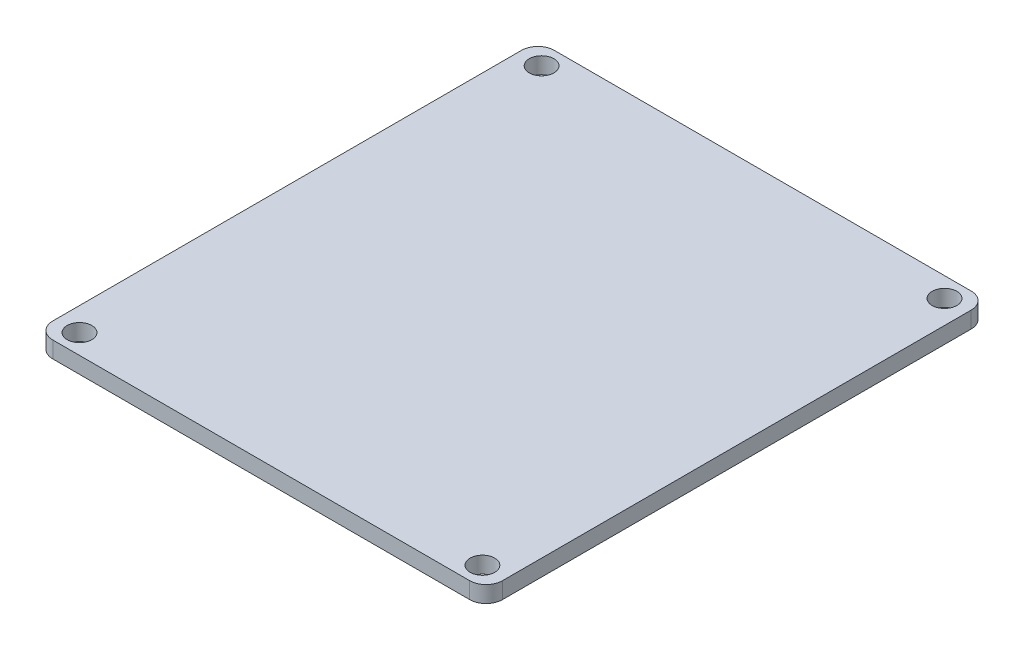
SolidWorks part; units mm, degrees
material "A-玻璃纤维"
ref_plane "前视基准面" through (0, 0, 0) normal (0, 0, 1) x (1, 0, 0)
ref_plane "上视基准面" through (0, 0, 0) normal (0, 1, 0) x (1, 0, 0)
ref_plane "右视基准面" through (0, 0, 0) normal (1, 0, 0) x (0, 0, -1)
sketch "草图1" plane through (0, 0, 0) normal (0, 1, 0) x (1, 0, 0)
  line L1 (-27.35, 30.5) -> (27.35, 30.5)
  line L2 (-27.35, 30.5) -> (-27.35, -30.5)
  line L3 (-27.35, -30.5) -> (27.35, -30.5)
  line L4 (27.35, 30.5) -> (27.35, -30.5)
  line L5 (0, -30.5) -> (0, 30.5) construction
  line L6 (-27.35, 0) -> (27.35, 0) construction
  circle A0 centre (-24.5, 28.1) radius 1.5
  circle A1 centre (-24.5, -28.1) radius 1.5
  circle A2 centre (24.5, 28.1) radius 1.5
  circle A3 centre (24.5, -28.1) radius 1.5
  point P0 (0, 0)
  dimension "D3" = 3
  dimension "D4" = 56.2
  dimension "D5" = 49
  dimension "D1" = 61
  dimension "D2" = 54.7
extrude "凸台-拉伸1" add sketch "草图1" along normal blind 2
fillet "圆角1" radius 2 4 edges at (-27.35, 1, 30.5) (-27.35, 1, -30.5) (27.35, 1, -30.5) (27.35, 1, 30.5)
